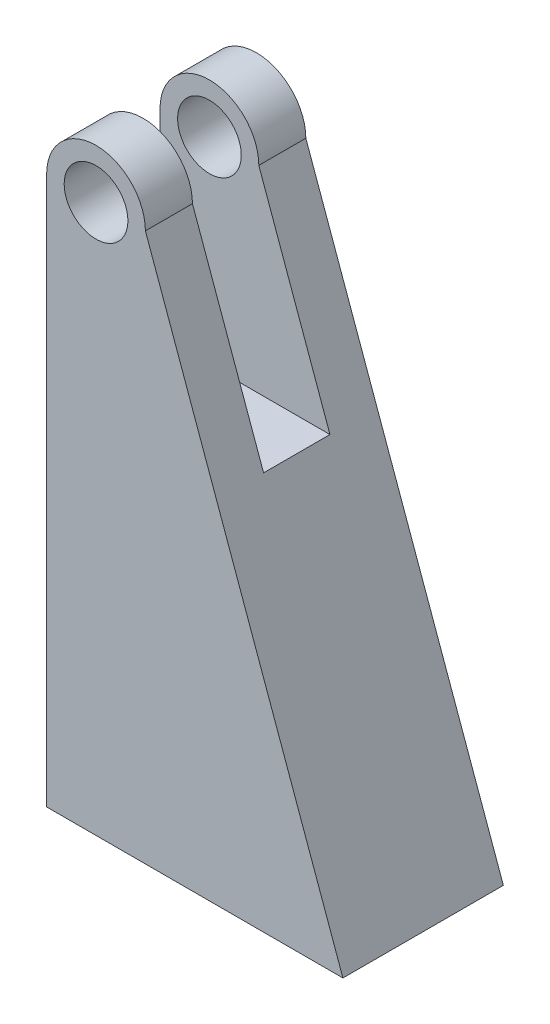
SolidWorks part; units mm, degrees
material "ABS"
ref_plane "Plano frontal" through (0, 0, 0) normal (0, 0, 1) x (1, 0, 0)
ref_plane "Plano superior" through (0, 0, 0) normal (0, 1, 0) x (1, 0, 0)
ref_plane "Plano direito" through (0, 0, 0) normal (1, 0, 0) x (0, 0, -1)
sketch "Esboço1" plane through (0, 0, 0) normal (0, 0, 1) x (1, 0, 0)
  line L0 (-5, 12.7594) -> (5, 12.7594) construction
  line L1 (5, -12.7594) -> (-5, -12.7594)
  line L2 (5, -12.7594) -> (5, 12.7594)
  line L4 (-5, -12.7594) -> (-5, 12.7594)
  line L5 (5, -12.7594) -> (-5, 12.7594) construction
  line L6 (5, 12.7594) -> (-5, -12.7594) construction
  line L7 (5, 12.7594) -> (25, -42.7594)
  line L8 (25, -42.7594) -> (-5, -42.7594)
  line L9 (-5, -42.7594) -> (-5, -12.7594)
  arc A0 (-5, 12.7594) -> (5, 12.7594) centre (0, 12.7594) cw
  point P0 (0, 0)
  point P7 (0, 12.7594)
  point P8 (0, 0)
  dimension "D1" = 5
  dimension "D2" = 25.5188
  dimension "D3" = 30
  dimension "D4" = 30
extrude "Ressalto-extrusão1" add sketch "Esboço1" along normal blind 16.0875 and the other way blind 0.1584 contours A0 L4 L1 L2 | L9 L8 L7 L2 L1
sketch "Esboço2" plane through (-5, 0, 0) normal (-1, 0, 0) x (0, 0, 1)
  line L0 (16.0875, 17.7594) -> (-0.1584, 17.7594) construction
  line L1 (4.6041, 17.7594) -> (11.325, 17.7594)
  line L2 (4.6041, 17.7594) -> (4.6041, -7.2406)
  line L3 (4.6041, -7.2406) -> (11.325, -7.2406)
  line L4 (11.325, 17.7594) -> (11.325, -7.2406)
  line L5 (11.325, -7.2406) -> (16.0875, -7.2406) construction
  line L7 (4.6041, -7.2406) -> (-0.1584, -7.2406) construction
  line L9 (16.0875, -42.7594) -> (16.0875, 12.7594) construction
  line L10 (-0.1584, -42.7594) -> (-0.1584, 12.7594) construction
  point P8 (0, 0)
  point P11 (0, 0)
  dimension "D1" = 25
  dimension "D2" = 4.7625
extrude "Corte-extrusão1" cut sketch "Esboço2" against normal through all
sketch "Esboço3" plane through (0, 0, -0.1584) normal (0, 0, -1) x (-1, 0, 0)
  circle A0 centre (0, 12.7594) radius 3.225
  dimension "D1" = 6.45
extrude "Corte-extrusão2" cut sketch "Esboço3" against normal through all
